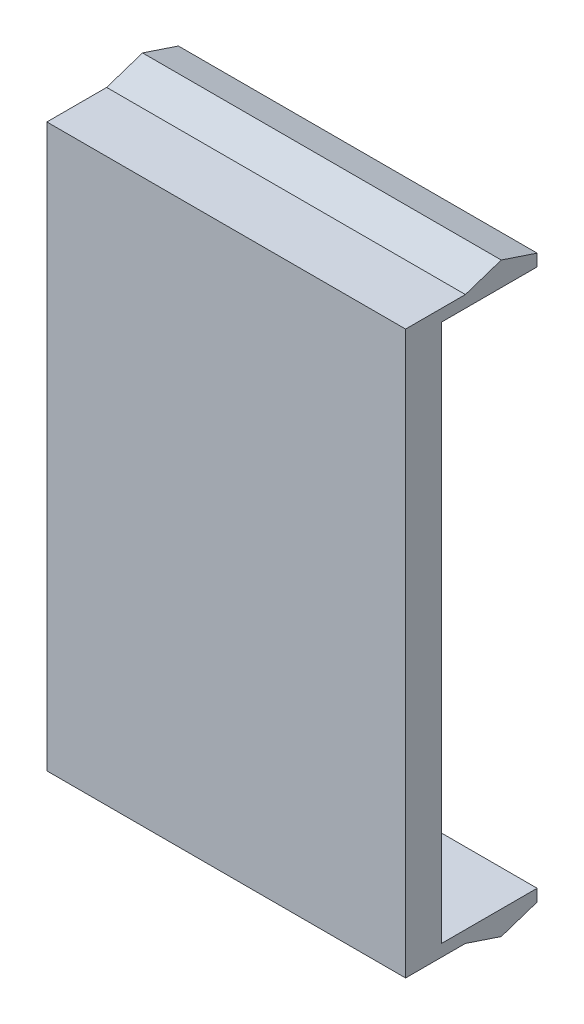
SolidWorks part; units mm, degrees
ref_plane "前视基准面" through (0, 0, 0) normal (0, 0, 1) x (1, 0, 0)
ref_plane "上视基准面" through (0, 0, 0) normal (0, 1, 0) x (1, 0, 0)
ref_plane "右视基准面" through (0, 0, 0) normal (1, 0, 0) x (0, 0, -1)
other "Configuration Table"
sketch "草图1" plane through (0, 0, 0) normal (0, 0, 1) x (1, 0, 0)
  line L5 (-15, -23.5) -> (15, -23.5)
  line L6 (-15, -23.5) -> (-15, 23.5)
  line L7 (-15, 23.5) -> (15, 23.5)
  line L8 (15, -23.5) -> (15, 23.5)
  line L9 (0, 23.5) -> (0, -23.5) construction
  line L10 (-15, 0) -> (15, 0) construction
  point P0 (0, 0)
  dimension "D1" = 47
  dimension "D2" = 30
extrude "凸台-拉伸1" add sketch "草图1" along normal blind 3
sketch "草图2" plane through (0, 0, 0) normal (0, 0, -1) x (-1, 0, 0)
  line L1 (-15, -22.5) -> (15, -22.5)
  line L2 (-15, -22.5) -> (-15, 22.5)
  line L3 (-15, 22.5) -> (15, 22.5)
  line L4 (-15, 23.5) -> (-15, -23.5)
  line L5 (-15, -23.5) -> (15, -23.5)
  line L6 (15, -23.5) -> (15, 23.5)
  line L7 (15, 23.5) -> (-15, 23.5)
  line L8 (-15, 23.5) -> (-15, -23.5)
  line L9 (-15, -23.5) -> (15, -23.5)
  line L10 (15, -23.5) -> (15, 23.5)
  line L11 (15, 23.5) -> (-15, 23.5)
  line L12 (15, -22.5) -> (15, 22.5)
  line L13 (0, 22.5) -> (0, -22.5) construction
  line L14 (-15, 0) -> (15, 0) construction
  point P2 (0, 0)
  line M9 (-15, 23.5) -> (-15, -23.5)
  line M10 (-15, -23.5) -> (15, -23.5)
  line M11 (15, -23.5) -> (15, 23.5)
  line M12 (15, 23.5) -> (-15, 23.5)
  dimension "D2" = 1
  dimension "D1" = 0
extrude "凸台-拉伸2" add sketch "草图2" along normal blind 8 contours L3 M9 M11 M12 | L1 M9 M10 M11
sketch "草图3" plane through (15, 0, 0) normal (1, 0, 0) x (0, 0, -1)
  line L0 (8, 23.5) -> (5, 24.5)
  line L1 (5, 24.5) -> (2, 23.5)
  line L2 (-3, 0) -> (12.7923, 0)
  line L3 (2, 23.5) -> (8, 23.5)
  line L4 (2, -23.5) -> (8, -23.5)
  line L5 (5, -24.5) -> (2, -23.5)
  line L6 (8, -23.5) -> (5, -24.5)
  line L8 (-3, -23.5) -> (8, -23.5)
  line L9 (8, -23.5) -> (8, -22.5)
  line L10 (8, -22.5) -> (0, -22.5)
  line L11 (0, -22.5) -> (0, 22.5)
  line L12 (0, 22.5) -> (8, 22.5)
  line L13 (8, 22.5) -> (8, 23.5)
  line L14 (8, 23.5) -> (-3, 23.5)
  line L15 (-3, 23.5) -> (-3, -23.5)
  line L16 (-3, -23.5) -> (8, -23.5)
  line L17 (8, -23.5) -> (8, -22.5)
  line L18 (8, -22.5) -> (0, -22.5)
  line L19 (0, -22.5) -> (0, 22.5)
  line L20 (0, 22.5) -> (8, 22.5)
  line L21 (8, 22.5) -> (8, 23.5)
  line L22 (8, 23.5) -> (-3, 23.5)
  line L23 (-3, 23.5) -> (-3, -23.5)
  line M13 (-3, -23.5) -> (8, -23.5)
  line M19 (8, 23.5) -> (-3, 23.5)
  dimension "D2" = 5
  dimension "D3" = 1
  dimension "D1" = 0
extrude "凸台-拉伸3" add sketch "草图3" against normal through all contours L0 L1 M19 | L6 L5 M13
